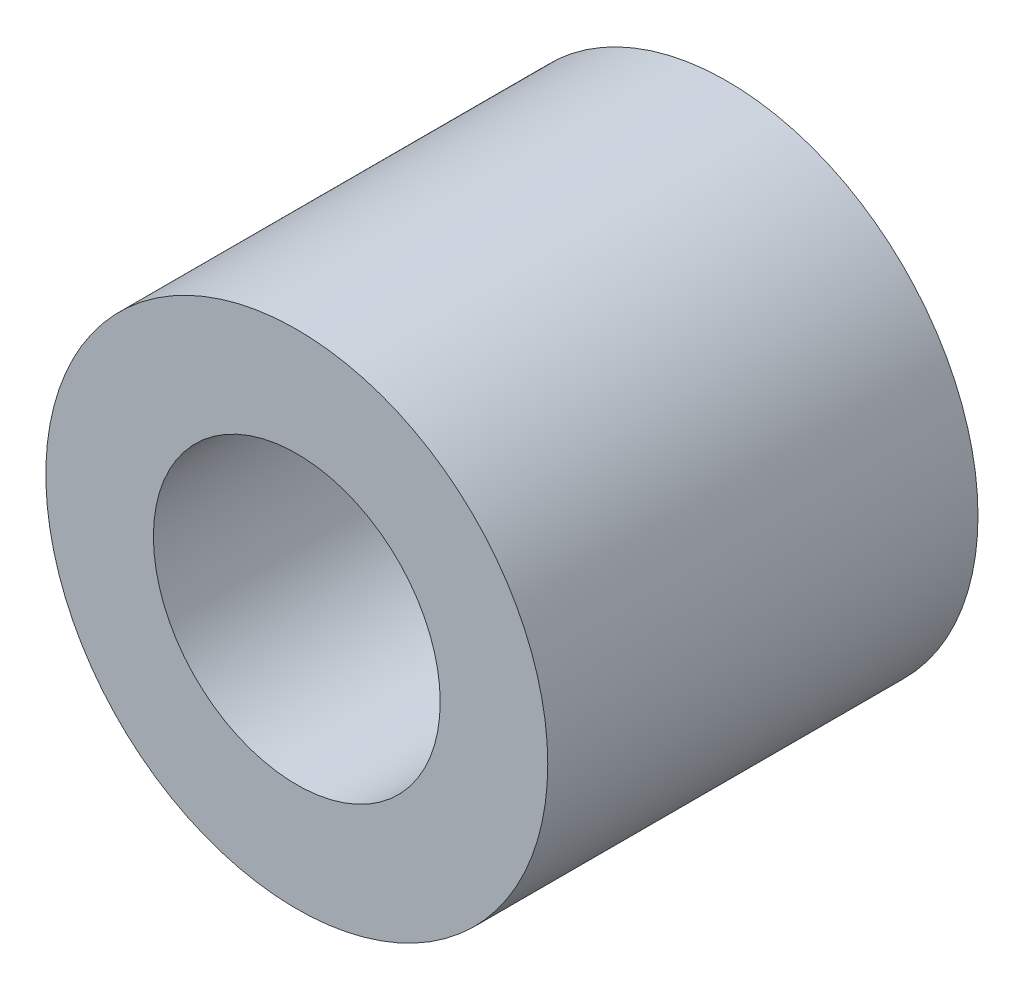
SolidWorks part; units mm, degrees
material "Brass"
ref_plane "Front Plane" through (0, 0, 0) normal (0, 0, 1) x (1, 0, 0)
ref_plane "Top Plane" through (0, 0, 0) normal (0, 1, 0) x (1, 0, 0)
ref_plane "Right Plane" through (0, 0, 0) normal (1, 0, 0) x (0, 0, -1)
sketch "Sketch1" plane through (0, 0, 0) normal (0, 0, 1) x (1, 0, 0)
  circle A0 centre (0, 0) radius 1
  circle A1 centre (0, 0) radius 1.75
  dimension "D1" = 2
  dimension "D2" = 3.5
extrude "Boss-Extrude1" add sketch "Sketch1" along normal blind 3
